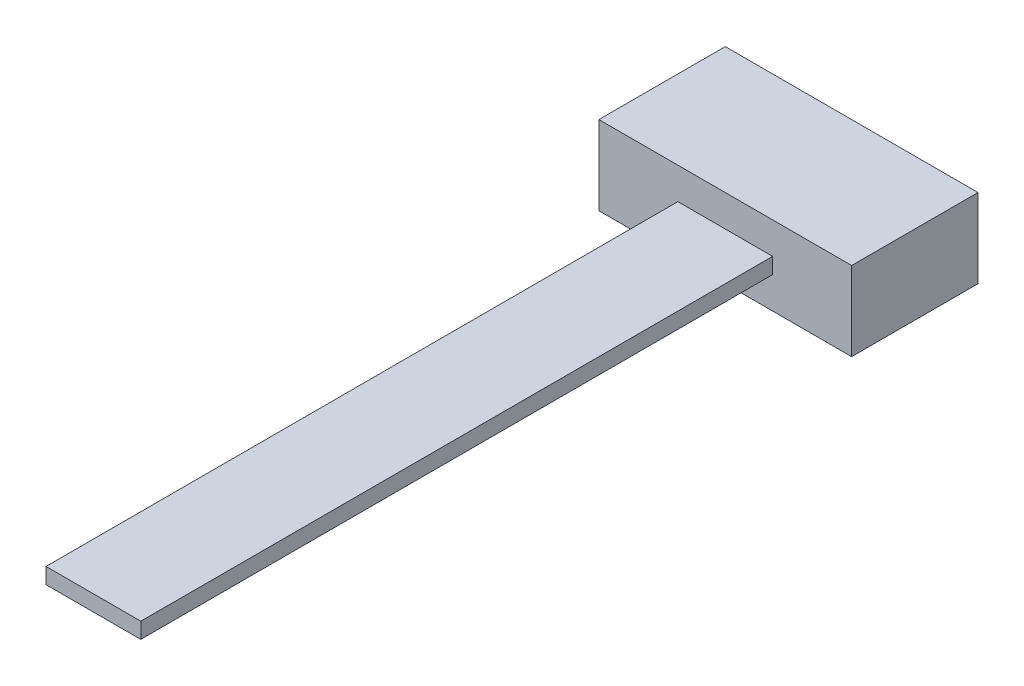
SolidWorks part; units mm, degrees
ref_plane "Front Plane" through (0, 0, 0) normal (0, 0, 1) x (1, 0, 0)
ref_plane "Top Plane" through (0, 0, 0) normal (0, 1, 0) x (1, 0, 0)
ref_plane "Right Plane" through (0, 0, 0) normal (1, 0, 0) x (0, 0, -1)
sketch "Sketch1" plane through (0, 0, 0) normal (0, 0, 1) x (1, 0, 0)
  line L0 (-15, -2.5) -> (15, -2.5)
  line L1 (-15, -2.5) -> (-15, 2.5)
  line L2 (15, -2.5) -> (15, 2.5)
  line L3 (-15, 2.5) -> (15, 2.5)
  line L4 (-15, -2.5) -> (15, 2.5) construction
  line L5 (15, -2.5) -> (-15, 2.5) construction
  point P1 (0, 0)
  dimension "D1" = 5
  dimension "D2" = 30
extrude "Boss-Extrude1" add sketch "Sketch1" along normal blind 200
sketch "Sketch2" plane through (0, 0, 0) normal (0, 0, 1) x (1, 0, 0)
  line L0 (-40, 12.5) -> (40, 12.5)
  line L1 (-40, 12.5) -> (-40, -12.5)
  line L2 (40, 12.5) -> (40, -12.5)
  line L3 (-40, -12.5) -> (40, -12.5)
  line L4 (-40, 12.5) -> (40, -12.5) construction
  line L5 (40, 12.5) -> (-40, -12.5) construction
  point P1 (0, 0)
  dimension "D1" = 25
  dimension "D2" = 80
extrude "Boss-Extrude2" add sketch "Sketch2" against normal blind 40
